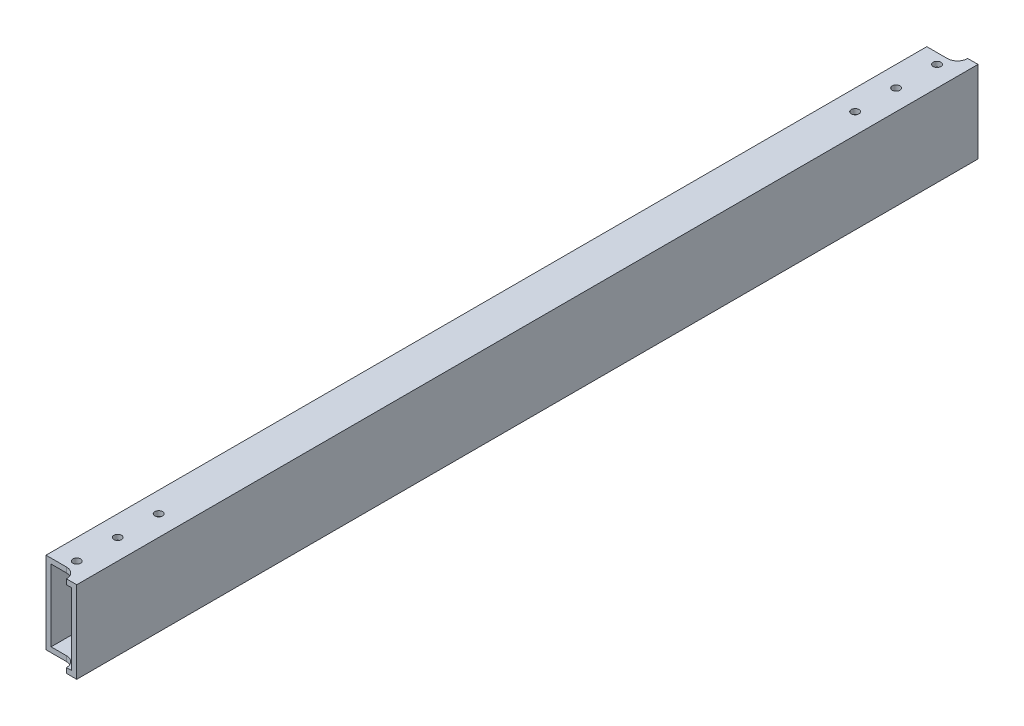
SolidWorks part; units mm, degrees
ref_plane "Front Plane" through (0, 0, 0) normal (0, 0, 1) x (1, 0, 0)
ref_plane "Top Plane" through (0, 0, 0) normal (0, 1, 0) x (1, 0, 0)
ref_plane "Right Plane" through (0, 0, 0) normal (1, 0, 0) x (0, 0, -1)
sketch "Sketch1" plane through (0, 0, 0) normal (0, 0, 1) x (1, 0, 0)
  line L1 (-12.7, 25.4) -> (12.7, 25.4)
  line L2 (-12.7, 25.4) -> (-12.7, -25.4)
  line L3 (-12.7, -25.4) -> (12.7, -25.4)
  line L4 (12.7, 25.4) -> (12.7, -25.4)
  line L5 (0, -25.4) -> (0, 25.4) construction
  line L6 (-12.7, 0) -> (12.7, 0) construction
  point P0 (0, 0)
  dimension "D1" = 25.4
  dimension "D2" = 50.8
extrude "Boss-Extrude1" add sketch "Sketch1" along normal mid plane 558.8
shell "Shell1" thickness 3.175
sketch "Sketch3" plane through (0, 25.4, 0) normal (0, 1, 0) x (1, 0, 0)
  line L3 (6.35, 279.4) -> (-12.7, 279.4)
  line L4 (-12.7, 279.4) -> (-12.7, 273.05)
  line L5 (-12.7, -279.4) -> (-12.7, 279.4) construction
  line L6 (-12.7, 273.05) -> (0, 273.05)
  line L7 (0, 0) -> (77.7351, 0) construction
  line L8 (-12.7, -273.05) -> (0, -273.05)
  line L9 (-12.7, -279.4) -> (-12.7, -273.05)
  line L10 (6.35, -279.4) -> (-12.7, -279.4)
  circle A0 centre (0, 279.4) radius 4.7625 construction
  circle A1 centre (0, 266.7) radius 2.3813
  circle A2 centre (0, 241.3) radius 2.3813
  arc A3 (6.35, 279.4) -> (0, 273.05) centre (0, 279.4) cw
  circle A4 centre (0, 215.9) radius 2.3813
  circle A5 centre (0, -279.4) radius 4.7625 construction
  circle A6 centre (0, -215.9) radius 2.3813
  arc A7 (6.35, -279.4) -> (0, -273.05) centre (0, -279.4) ccw
  circle A8 centre (0, -241.3) radius 2.3813
  circle A9 centre (0, -266.7) radius 2.3813
  dimension "D1" = 9.525
  dimension "D2" = 4.7625
  dimension "D4" = 25.4
  dimension "D5" = 6.35
  dimension "D6" = 25.4
  dimension "D3" = 12.7
extrude "Cut-Extrude1" cut sketch "Sketch3" against normal through all
